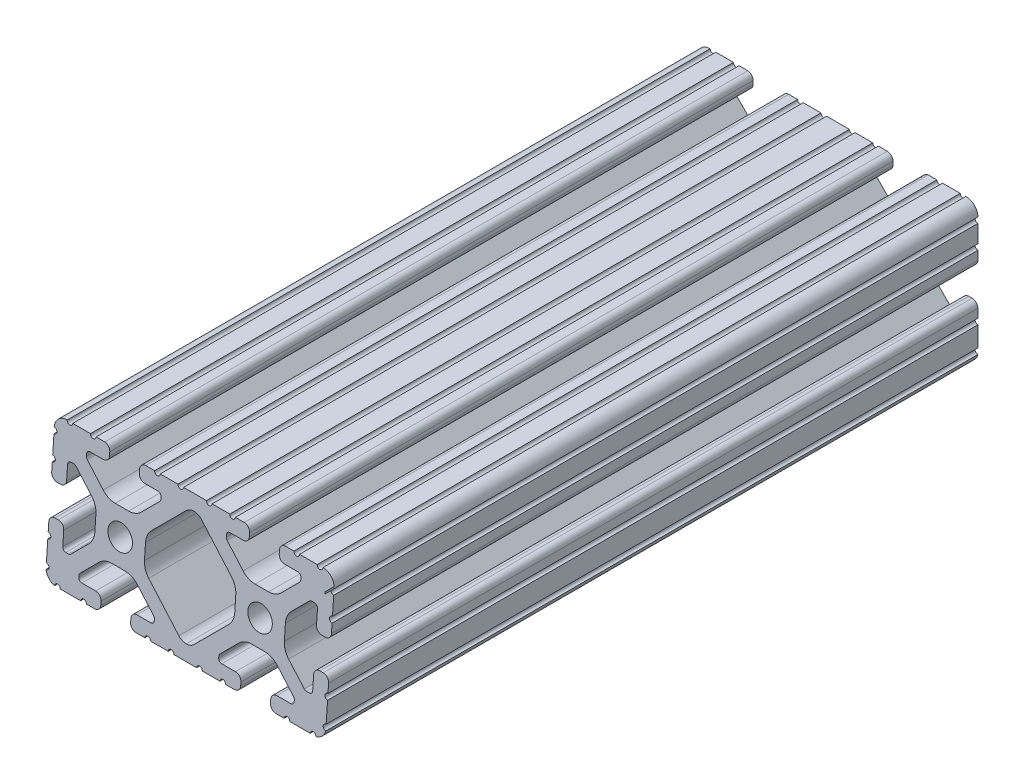
SolidWorks part; units mm, degrees
material "6005A-T61"
ref_plane "Front Plane" through (0, 0, 0) normal (0, 0, 1) x (1, 0, 0)
ref_plane "Top Plane" through (0, 0, 0) normal (0, 1, 0) x (1, 0, 0)
ref_plane "Right Plane" through (0, 0, 0) normal (1, 0, 0) x (0, 0, -1)
sketch "Sketch1" plane through (0, 0, 0) normal (0, 0, 1) x (1, 0, 0)
  line L0 (-3.1211, -19.05) -> (3.1211, -19.05)
  line L1 (-38.1, 10.287) -> (-38.1, 14.3752)
  line L2 (0, -34.5561) -> (0, 32.8014) construction
  line L3 (-38.1, 0) -> (0, 0) construction
  line L4 (-38.1, 9.5497) -> (-38.1, 10.287)
  line L5 (-19.05, 19.05) -> (-19.05, -20.2827) construction
  line L6 (0, -15.1247) -> (0, -15.1131) construction
  line L7 (9.1761, 12.9058) -> (13.8525, 8.2294)
  line L8 (8.9158, 14.097) -> (8.9158, 13.5344)
  line L9 (13.4112, 14.986) -> (9.8048, 14.986)
  line L10 (14.986, 17.4968) -> (14.986, 16.5608)
  line L11 (10.9975, 19.05) -> (13.4328, 19.05)
  line L12 (8.6331, 19.05) -> (9.4735, 19.05)
  line L13 (4.6451, 19.05) -> (8.6331, 19.05)
  line L14 (31.792, 10.0266) -> (27.1976, 5.4321)
  line L15 (33.147, 10.287) -> (32.4207, 10.287)
  line L16 (29.2071, 19.05) -> (33.2963, 19.05)
  line L17 (28.4698, 19.05) -> (29.2071, 19.05)
  line L18 (-38.1, 5.6388) -> (-38.1, 8.0257)
  line L19 (24.5589, 19.05) -> (26.9458, 19.05)
  line L20 (23.114, 16.5608) -> (23.114, 17.4806)
  line L21 (28.2952, 14.986) -> (24.6888, 14.986)
  line L22 (29.1842, 13.5344) -> (29.1842, 14.097)
  line L23 (-34.036, 9.398) -> (-34.036, 5.6388)
  line L24 (-35.6108, 4.064) -> (-36.5252, 4.064)
  line L25 (24.2475, 8.2294) -> (28.9239, 12.9058)
  line L26 (25.8064, -2.0735) -> (25.8064, 2.0735)
  line L27 (35.6108, 4.064) -> (36.5252, 4.064)
  line L28 (34.036, 9.398) -> (34.036, 5.6388)
  line L29 (38.1, 5.6388) -> (38.1, 8.0257)
  line L30 (38.1, 9.5497) -> (38.1, 10.287)
  line L31 (38.1, 10.287) -> (38.1, 14.3752)
  line L32 (17.2111, 6.8382) -> (20.8889, 6.8382)
  line L33 (2.077, 14.2576) -> (10.9024, 5.4321)
  line L34 (-31.792, -10.0266) -> (-27.1976, -5.4321)
  line L35 (-33.147, -10.287) -> (-32.4207, -10.287)
  line L36 (-29.2071, -19.05) -> (-34.0473, -19.05)
  line L37 (-28.4698, -19.05) -> (-29.2071, -19.05)
  line L38 (-24.6888, -19.05) -> (-26.9458, -19.05)
  line L39 (12.2936, -2.0735) -> (12.2936, 2.0735)
  line L40 (-23.114, -16.5608) -> (-23.114, -17.4752)
  line L41 (-28.448, -14.986) -> (-24.6888, -14.986)
  line L42 (-29.337, -13.6872) -> (-29.337, -14.097)
  line L43 (2.077, -14.2576) -> (10.9024, -5.4321)
  line L44 (-3.1211, 19.05) -> (3.1211, 19.05)
  line L45 (8.763, -14.097) -> (8.763, -13.6872)
  line L46 (-24.2475, -8.2294) -> (-29.0766, -13.0586)
  line L47 (-35.6108, -4.064) -> (-36.5252, -4.064)
  line L48 (-34.036, -9.398) -> (-34.036, -5.6388)
  line L49 (-38.1, -5.6388) -> (-38.1, -8.0257)
  line L50 (-38.1, -9.5497) -> (-38.1, -10.287)
  line L51 (-38.1, -10.287) -> (-38.1, -15.036)
  line L52 (17.2111, -6.8382) -> (20.8889, -6.8382)
  line L53 (38.1, -10.287) -> (38.1, -15.036)
  line L54 (38.1, -9.5497) -> (38.1, -10.287)
  line L55 (38.1, -5.6388) -> (38.1, -8.0257)
  line L56 (34.036, -9.398) -> (34.036, -5.6388)
  line L57 (35.6108, -4.064) -> (36.5252, -4.064)
  line L58 (24.2475, -8.2294) -> (29.0766, -13.0586)
  line L59 (29.337, -13.6872) -> (29.337, -14.097)
  line L60 (-17.2111, -6.8382) -> (-20.8889, -6.8382)
  line L61 (-9.0234, -13.0586) -> (-13.8525, -8.2294)
  line L62 (-8.763, -14.097) -> (-8.763, -13.6872)
  line L63 (-13.4112, -14.986) -> (-9.652, -14.986)
  line L64 (-14.986, -17.4752) -> (-14.986, -16.5608)
  line L65 (-10.9975, -19.05) -> (-13.4112, -19.05)
  line L66 (28.448, -14.986) -> (24.6888, -14.986)
  line L67 (23.114, -16.5608) -> (23.114, -17.4752)
  line L68 (24.6888, -19.05) -> (26.9458, -19.05)
  line L69 (28.4698, -19.05) -> (29.2071, -19.05)
  line L70 (29.2071, -19.05) -> (34.0473, -19.05)
  line L71 (-8.6331, -19.05) -> (-9.4735, -19.05)
  line L72 (33.147, -10.287) -> (32.4207, -10.287)
  line L73 (31.792, -10.0266) -> (27.1976, -5.4321)
  line L74 (-4.6451, -19.05) -> (-8.6331, -19.05)
  line L75 (9.0234, -13.0586) -> (13.8525, -8.2294)
  line L76 (13.4112, -14.986) -> (9.652, -14.986)
  line L77 (-2.077, -14.2576) -> (-10.9024, -5.4321)
  line L78 (14.986, -17.4752) -> (14.986, -16.5608)
  line L79 (10.9975, -19.05) -> (13.4112, -19.05)
  line L80 (4.6451, -19.05) -> (8.6331, -19.05)
  line L81 (8.6331, -19.05) -> (9.4735, -19.05)
  line L83 (-12.2936, -2.0735) -> (-12.2936, 2.0735)
  line L84 (-25.8064, -2.0735) -> (-25.8064, 2.0735)
  line L85 (-2.077, 14.2576) -> (-10.9024, 5.4321)
  line L87 (-4.6451, 19.05) -> (-8.6331, 19.05)
  line L88 (-8.6331, 19.05) -> (-9.4735, 19.05)
  line L89 (-10.9975, 19.05) -> (-13.4328, 19.05)
  line L90 (-14.986, 17.4968) -> (-14.986, 16.5608)
  line L91 (-13.4112, 14.986) -> (-9.8048, 14.986)
  line L92 (-8.9158, 14.097) -> (-8.9158, 13.5344)
  line L93 (-9.1761, 12.9058) -> (-13.8525, 8.2294)
  line L94 (-17.2111, 6.8382) -> (-20.8889, 6.8382)
  line L95 (-24.2475, 8.2294) -> (-28.9239, 12.9058)
  line L96 (-29.1842, 13.5344) -> (-29.1842, 14.097)
  line L97 (-28.2952, 14.986) -> (-24.6888, 14.986)
  line L98 (-23.114, 16.5608) -> (-23.114, 17.4806)
  line L99 (-24.5589, 19.05) -> (-26.9458, 19.05)
  line L100 (-28.4698, 19.05) -> (-29.2071, 19.05)
  line L101 (-29.2071, 19.05) -> (-33.2963, 19.05)
  line L109 (-33.147, 10.287) -> (-32.4207, 10.287)
  line L165 (-31.792, 10.0266) -> (-27.1976, 5.4321)
  arc A0 (-38.1376, 15.8983) -> (-38.1, 14.3752) centre (-38.1, 15.1372) cw
  arc A1 (-38.1, 9.5497) -> (-38.1, 8.0257) centre (-38.1, 8.7877) cw
  arc A2 (9.1761, 12.9058) -> (8.9158, 13.5344) centre (9.8048, 13.5344) cw
  arc A3 (8.9158, 14.097) -> (9.8048, 14.986) centre (9.8048, 14.097) cw
  arc A4 (-36.5252, 4.064) -> (-38.1, 5.6388) centre (-36.5252, 5.6388) cw
  arc A5 (14.986, 16.5608) -> (13.4112, 14.986) centre (13.4112, 16.5608) cw
  arc A6 (13.4328, 19.05) -> (14.986, 17.4968) centre (13.4328, 17.4968) cw
  arc A7 (10.9975, 19.05) -> (9.4735, 19.05) centre (10.2355, 19.05) cw
  arc A8 (4.6451, 19.05) -> (3.1211, 19.05) centre (3.8831, 19.05) cw
  arc A9 (0, 15.1131) -> (2.077, 14.2576) centre (0.0116, 12.1921) cw
  arc A10 (25.8064, 2.0735) -> (27.1976, 5.4321) centre (30.5562, 2.0735) cw
  arc A11 (31.792, 10.0266) -> (32.4207, 10.287) centre (32.4207, 9.398) cw
  arc A12 (33.147, 10.287) -> (34.036, 9.398) centre (33.147, 9.398) cw
  arc A13 (34.8195, 19.0968) -> (38.1376, 15.8983) centre (34.903, 15.8631) cw
  arc A14 (34.8195, 19.0968) -> (33.2963, 19.05) centre (34.0579, 19.0734) cw
  arc A15 (28.4698, 19.05) -> (26.9458, 19.05) centre (27.7078, 19.05) cw
  arc A16 (23.114, 17.4806) -> (24.5589, 19.05) centre (24.6888, 17.4806) cw
  arc A17 (24.6888, 14.986) -> (23.114, 16.5608) centre (24.6888, 16.5608) cw
  arc A18 (28.2952, 14.986) -> (29.1842, 14.097) centre (28.2952, 14.097) cw
  arc A19 (29.1842, 13.5344) -> (28.9239, 12.9058) centre (28.2952, 13.5344) cw
  arc A20 (-35.5713, -19.05) -> (-38.1, -16.56) centre (-34.9455, -15.8855) cw
  arc A21 (34.036, 5.6388) -> (35.6108, 4.064) centre (35.6108, 5.6388) ccw
  arc A22 (36.5252, 4.064) -> (38.1, 5.6388) centre (36.5252, 5.6388) ccw
  arc A23 (38.1, 9.5497) -> (38.1, 8.0257) centre (38.1, 8.7877) ccw
  arc A24 (24.2475, 8.2294) -> (20.8889, 6.8382) centre (20.8889, 11.588) cw
  arc A25 (17.2111, 6.8382) -> (13.8525, 8.2294) centre (17.2111, 11.588) cw
  arc A26 (10.9024, 5.4321) -> (12.2936, 2.0735) centre (7.5438, 2.0735) cw
  arc A27 (0, -15.1131) -> (2.077, -14.2576) centre (0.0116, -12.1921) ccw
  arc A28 (-34.036, 5.6388) -> (-35.6108, 4.064) centre (-35.6108, 5.6388) cw
  arc A29 (-25.8064, -2.0735) -> (-27.1976, -5.4321) centre (-30.5562, -2.0735) cw
  arc A30 (-31.792, -10.0266) -> (-32.4207, -10.287) centre (-32.4207, -9.398) cw
  arc A31 (-33.147, -10.287) -> (-34.036, -9.398) centre (-33.147, -9.398) cw
  arc A33 (-35.5713, -19.05) -> (-34.0473, -19.05) centre (-34.8093, -19.05) cw
  arc A34 (-28.4698, -19.05) -> (-26.9458, -19.05) centre (-27.7078, -19.05) cw
  arc A35 (10.9024, -5.4321) -> (12.2936, -2.0735) centre (7.5438, -2.0735) ccw
  circle A36 centre (19.05, 0) radius 3.3274
  arc A37 (-23.114, -17.4752) -> (-24.6888, -19.05) centre (-24.6888, -17.4752) cw
  arc A38 (-24.6888, -14.986) -> (-23.114, -16.5608) centre (-24.6888, -16.5608) cw
  arc A39 (-28.448, -14.986) -> (-29.337, -14.097) centre (-28.448, -14.097) cw
  arc A40 (-29.337, -13.6872) -> (-29.0766, -13.0586) centre (-28.448, -13.6872) cw
  arc A41 (-24.2475, -8.2294) -> (-20.8889, -6.8382) centre (-20.8889, -11.588) cw
  arc A42 (-34.036, -5.6388) -> (-35.6108, -4.064) centre (-35.6108, -5.6388) ccw
  arc A43 (-36.5252, -4.064) -> (-38.1, -5.6388) centre (-36.5252, -5.6388) ccw
  arc A44 (-38.1, -9.5497) -> (-38.1, -8.0257) centre (-38.1, -8.7877) ccw
  arc A45 (-38.1, -16.56) -> (-38.1, -15.036) centre (-38.1, -15.798) ccw
  arc A46 (38.1, -16.56) -> (38.1, -15.036) centre (38.1, -15.798) cw
  arc A47 (38.1, -9.5497) -> (38.1, -8.0257) centre (38.1, -8.7877) cw
  arc A48 (36.5252, -4.064) -> (38.1, -5.6388) centre (36.5252, -5.6388) cw
  arc A49 (34.036, -5.6388) -> (35.6108, -4.064) centre (35.6108, -5.6388) cw
  arc A50 (24.2475, -8.2294) -> (20.8889, -6.8382) centre (20.8889, -11.588) ccw
  arc A51 (29.337, -13.6872) -> (29.0766, -13.0586) centre (28.448, -13.6872) ccw
  arc A52 (28.448, -14.986) -> (29.337, -14.097) centre (28.448, -14.097) ccw
  arc A53 (24.6888, -14.986) -> (23.114, -16.5608) centre (24.6888, -16.5608) ccw
  arc A54 (-17.2111, -6.8382) -> (-13.8525, -8.2294) centre (-17.2111, -11.588) cw
  arc A55 (-9.0234, -13.0586) -> (-8.763, -13.6872) centre (-9.652, -13.6872) cw
  arc A56 (-8.763, -14.097) -> (-9.652, -14.986) centre (-9.652, -14.097) cw
  arc A57 (-14.986, -16.5608) -> (-13.4112, -14.986) centre (-13.4112, -16.5608) cw
  arc A58 (-13.4112, -19.05) -> (-14.986, -17.4752) centre (-13.4112, -17.4752) cw
  arc A59 (-10.9975, -19.05) -> (-9.4735, -19.05) centre (-10.2355, -19.05) cw
  arc A60 (-4.6451, -19.05) -> (-3.1211, -19.05) centre (-3.8831, -19.05) cw
  arc A61 (23.114, -17.4752) -> (24.6888, -19.05) centre (24.6888, -17.4752) ccw
  arc A62 (28.4698, -19.05) -> (26.9458, -19.05) centre (27.7078, -19.05) ccw
  arc A63 (35.5713, -19.05) -> (34.0473, -19.05) centre (34.8093, -19.05) ccw
  arc A64 (35.5713, -19.05) -> (38.1, -16.56) centre (34.9379, -15.8778) ccw
  arc A65 (33.147, -10.287) -> (34.036, -9.398) centre (33.147, -9.398) ccw
  arc A66 (31.792, -10.0266) -> (32.4207, -10.287) centre (32.4207, -9.398) ccw
  arc A67 (-10.9024, -5.4321) -> (-12.2936, -2.0735) centre (-7.5438, -2.0735) cw
  arc A68 (0, -15.1131) -> (-2.077, -14.2576) centre (-0.0116, -12.1921) cw
  arc A69 (0, 15.1131) -> (-2.077, 14.2576) centre (-0.0116, 12.1921) ccw
  arc A70 (-10.9024, 5.4321) -> (-12.2936, 2.0735) centre (-7.5438, 2.0735) ccw
  arc A71 (25.8064, -2.0735) -> (27.1976, -5.4321) centre (30.5562, -2.0735) ccw
  arc A72 (9.0234, -13.0586) -> (8.763, -13.6872) centre (9.652, -13.6872) ccw
  arc A73 (8.763, -14.097) -> (9.652, -14.986) centre (9.652, -14.097) ccw
  arc A74 (17.2111, -6.8382) -> (13.8525, -8.2294) centre (17.2111, -11.588) ccw
  arc A75 (13.4112, -19.05) -> (14.986, -17.4752) centre (13.4112, -17.4752) ccw
  arc A76 (14.986, -16.5608) -> (13.4112, -14.986) centre (13.4112, -16.5608) ccw
  arc A77 (-4.6451, 19.05) -> (-3.1211, 19.05) centre (-3.8831, 19.05) ccw
  arc A78 (-10.9975, 19.05) -> (-9.4735, 19.05) centre (-10.2355, 19.05) ccw
  arc A79 (-13.4328, 19.05) -> (-14.986, 17.4968) centre (-13.4328, 17.4968) ccw
  arc A80 (-14.986, 16.5608) -> (-13.4112, 14.986) centre (-13.4112, 16.5608) ccw
  arc A81 (-8.9158, 14.097) -> (-9.8048, 14.986) centre (-9.8048, 14.097) ccw
  arc A82 (-9.1761, 12.9058) -> (-8.9158, 13.5344) centre (-9.8048, 13.5344) ccw
  arc A83 (-17.2111, 6.8382) -> (-13.8525, 8.2294) centre (-17.2111, 11.588) ccw
  arc A84 (-24.2475, 8.2294) -> (-20.8889, 6.8382) centre (-20.8889, 11.588) ccw
  arc A85 (-29.1842, 13.5344) -> (-28.9239, 12.9058) centre (-28.2952, 13.5344) ccw
  arc A86 (-28.2952, 14.986) -> (-29.1842, 14.097) centre (-28.2952, 14.097) ccw
  arc A87 (-24.6888, 14.986) -> (-23.114, 16.5608) centre (-24.6888, 16.5608) ccw
  arc A88 (-23.114, 17.4806) -> (-24.5589, 19.05) centre (-24.6888, 17.4806) ccw
  arc A89 (-28.4698, 19.05) -> (-26.9458, 19.05) centre (-27.7078, 19.05) ccw
  arc A90 (-34.8195, 19.0968) -> (-33.2963, 19.05) centre (-34.0579, 19.0734) ccw
  arc A91 (-34.8195, 19.0968) -> (-38.1376, 15.8983) centre (-34.903, 15.8631) ccw
  arc A92 (4.6451, -19.05) -> (3.1211, -19.05) centre (3.8831, -19.05) ccw
  arc A93 (10.9975, -19.05) -> (9.4735, -19.05) centre (10.2355, -19.05) ccw
  arc A94 (38.1376, 15.8983) -> (38.1, 14.3752) centre (38.1, 15.1372) ccw
  arc A96 (-33.147, 10.287) -> (-34.036, 9.398) centre (-33.147, 9.398) ccw
  arc A97 (-31.792, 10.0266) -> (-32.4207, 10.287) centre (-32.4207, 9.398) ccw
  arc A98 (-25.8064, 2.0735) -> (-27.1976, 5.4321) centre (-30.5562, 2.0735) ccw
  circle A101 centre (-19.05, 0) radius 3.3274
  point P34 (0, 19.05)
  point P79 (25.6765, 0)
  point P274 (0, -19.05)
  point P282 (-25.6765, 0)
  point P283 (-12.2936, 0)
  dimension "D1" = 38.1
  dimension "D4" = 6.6548
  dimension "D10" = 4.064
  dimension "D2" = 76.2
  dimension "D3" = 38.1
  dimension "D5" = 8.128
  dimension "D6" = 20.574
  dimension "D7" = 12.2936
  dimension "D8" = 4.064
  dimension "D9" = 4.064
extrude "Extrude1" add sketch "Sketch1" against normal blind 177.8
sketch "Sketch2" plane through (38.1, 0, 0) normal (1, 0, 0) x (0, 0, -1)
  line L0 (0, -19.05) -> (2.6676, 19.0979)
  line L1 (177.8, 19.0979) -> (0, 19.0979) construction
  line L2 (2.6676, 19.0979) -> (0, 19.0979)
  line L3 (0, 19.0979) -> (0, -19.05)
  dimension "D1" = 4
extrude "Cut-Extrude1" cut sketch "Sketch2" against normal blind 127
